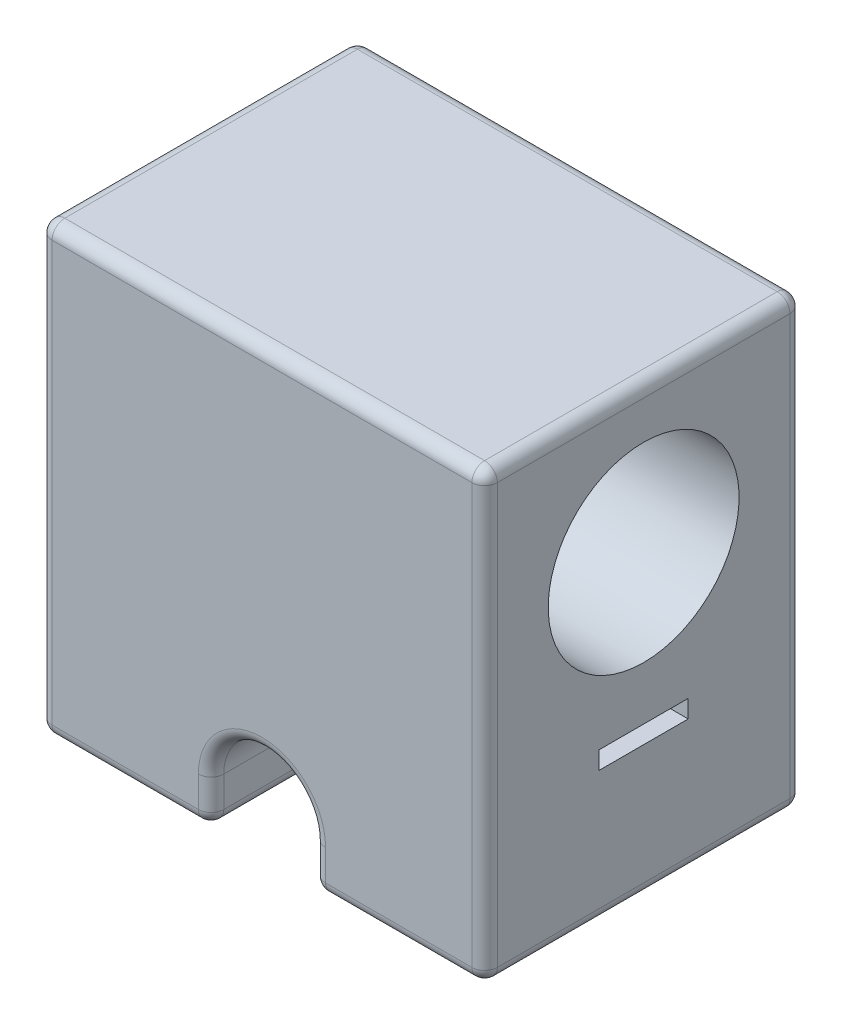
SolidWorks part; units mm, degrees
ref_plane "Piano frontale" through (0, 0, 0) normal (0, 0, 1) x (1, 0, 0)
ref_plane "Piano superiore" through (0, 0, 0) normal (0, 1, 0) x (1, 0, 0)
ref_plane "Piano destro" through (0, 0, 0) normal (1, 0, 0) x (0, 0, -1)
sketch "Schizzo1" plane through (0, 0, 0) normal (0, 0, 1) x (1, 0, 0)
  line L0 (-4, -14.0858) -> (-4, -16.5)
  line L1 (-17.5, 17.5) -> (17.5, 17.5)
  line L2 (-17.5, 17.5) -> (-17.5, -17.5)
  line L3 (-5, -17.5) -> (-17.5, -17.5)
  line L4 (17.5, 17.5) -> (17.5, -17.5)
  line L5 (4, -14.0858) -> (4, -16.5)
  line L6 (5, -17.5) -> (17.5, -17.5)
  arc A0 (4, -14.0858) -> (-4, -14.0858) centre (0, -14.0858) ccw
  arc A1 (4, -16.5) -> (5, -17.5) centre (5, -16.5) ccw
  arc A2 (-4, -16.5) -> (-5, -17.5) centre (-5, -16.5) cw
  point P5 (0, -10.0858)
  point P10 (0, -17.5)
  dimension "D3" = 8
  dimension "D4" = 1
  dimension "D1" = 35
  dimension "D2" = 35
  dimension "D5" = 12.5
  dimension "D6" = 7.4142
extrude "Estrusione-Estrusione1" add sketch "Schizzo1" along normal blind 25
sketch "Schizzo2" plane through (17.5, 0, 0) normal (1, 0, 0) x (0, 0, -1)
  line L0 (-25, 17.5) -> (0, 17.5) construction
  circle A0 centre (-12.5, 6) radius 7.5
  point P5 (-12.5, 13.5)
  point P6 (-12.5, 17.5)
  dimension "D1" = 15
  dimension "D2" = 4
extrude "Taglio-Estrusione1" cut sketch "Schizzo2" against normal through all
sketch "Schizzo3" plane through (17.5, 0, 0) normal (1, 0, 0) x (0, 0, -1)
  line L1 (-16, -5.6858) -> (-9, -5.6858)
  line L2 (-16, -5.6858) -> (-16, -7.0858)
  line L3 (-16, -7.0858) -> (-9, -7.0858)
  line L4 (-9, -5.6858) -> (-9, -7.0858)
  line L6 (-25, -17.5) -> (-25, 17.5) construction
  line L7 (0, -10.0858) -> (-25, -10.0858) construction
  circle A1 centre (-12.5, 6) radius 7.5 construction
  point P4 (-12.5, -1.5)
  dimension "D3" = 3
  dimension "D1" = 1.4
  dimension "D2" = 7
  dimension "D4" = 9
extrude "Taglio-Estrusione2" cut sketch "Schizzo3" against normal through all
fillet "Raccordo2" radius 1 24 edges at (-11.25, -17.5, 0) (-4.2929, -17.2071, 0) (-4, -15.2929, 0) (0, -10.0858, 0) (4, -15.2929, 0) (4.2929, -17.2071, 0) (-11.25, -17.5, 25) (-4.2929, -17.2071, 25) (-4, -15.2929, 25) (0, -10.0858, 25) (4, -15.2929, 25) (4.2929, -17.2071, 25) (-17.5, -17.5, 12.5) (-17.5, 0, 0) (-17.5, 17.5, 12.5) (-17.5, 0, 25) (17.5, -17.5, 12.5) (17.5, 0, 0) (17.5, 17.5, 12.5) (11.25, -17.5, 0) (11.25, -17.5, 25) (0, 17.5, 0) (0, 17.5, 25) (17.5, 0, 25)
